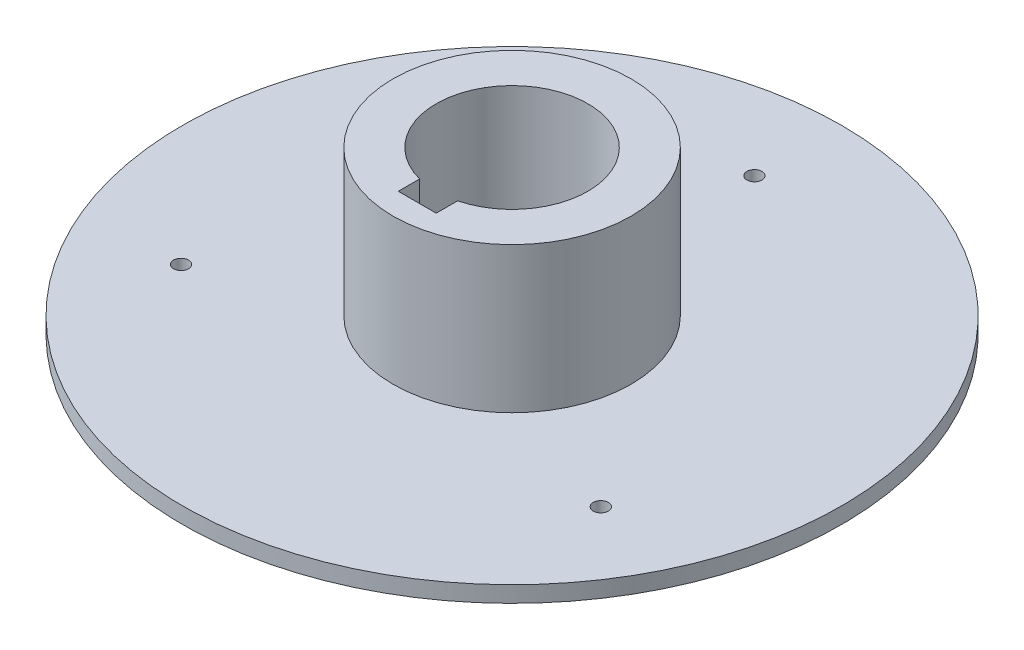
SolidWorks part; units mm, degrees
ref_plane "Front Plane" through (0, 0, 0) normal (0, 0, 1) x (1, 0, 0)
ref_plane "Top Plane" through (0, 0, 0) normal (0, 1, 0) x (1, 0, 0)
ref_plane "Right Plane" through (0, 0, 0) normal (1, 0, 0) x (0, 0, -1)
sketch "Sketch1" plane through (0, 0, 0) normal (0, 0, 1) x (1, 0, 0)
  line L0 (69.5121, 0) -> (16, 0)
  line L1 (16, 0) -> (16, 34.1234)
  line L2 (16, 34.1234) -> (25.0996, 34.1234)
  line L3 (25.0996, 34.1234) -> (25.0996, 3.4123)
  line L5 (69.5121, 0) -> (69.5121, 3.4123)
  line L6 (69.5121, 3.4123) -> (25.0996, 3.4123)
  line L7 (0, 0) -> (0, 18.7678)
  dimension "D1" = 16
  dimension "D2" = 9.0996
revolve "Revolve1" add sketch "Sketch1" angle 360 about L7
sketch "Sketch2" plane through (0, 3.4123, 0) normal (0, 1, 0) x (1, 0, 0)
  line L0 (0, 16) -> (0, 51.1125)
  circle A0 centre (0, 0) radius 16 construction
hole_wizard "1/8 (0.125) Diameter Hole1" positions "3DSketch1" profile "Sketch3" hole size "1/8" standard "ANSI Inch" end condition through all
sketch3d "3DSketch1"
  point P0 (0, 3.4123, -51.1125)
  point P5 (0, 3.4123, -51.1125)
  point P7 (0, 3.4123, -51.1125)
sketch "Sketch3" plane through (0, 3.4123, -51.1125) normal (1, 0, 0) x (0, 0, 1)
  line L0 (0, 0) -> (0, 3.4123)
  line L1 (0, 3.4123) -> (1.5875, 3.4123)
  line L2 (1.5875, 3.4123) -> (1.5875, 0)
  line L5 (1.5875, 0) -> (0, 0)
  line L11 (0, -6.35) -> (0, 107.95) construction
  dimension "Thru Hole Dia." = 3.175
  dimension "Thru Hole Depth" = 3.4123
pattern_circular "CirPattern2" count 3 every 120 about axis through (0, 0, 0) along (0, 1, 0) of "1/8 (0.125) Diameter Hole1"
pattern_circular "CirPattern1" count 3 every 120 about axis through (0, 3.4123, 0) along (0, -1, 0) of "1/8 (0.125) Diameter Hole1"
sketch "Sketch4" plane through (0, 34.1234, 0) normal (0, 1, 0) x (1, 0, 0)
  line L1 (0, -20) -> (4, -20)
  line L2 (0, -20) -> (-4, -20)
  line L3 (-4, -20) -> (-4, -14.2343)
  line L4 (-4, -14.2343) -> (4, -14.2343)
  line L5 (4, -14.2343) -> (4, -20)
  circle A0 centre (0, 0) radius 16 construction
  dimension "D1" = 20
extrude "Cut-Extrude2" cut sketch "Sketch4" against normal through all
